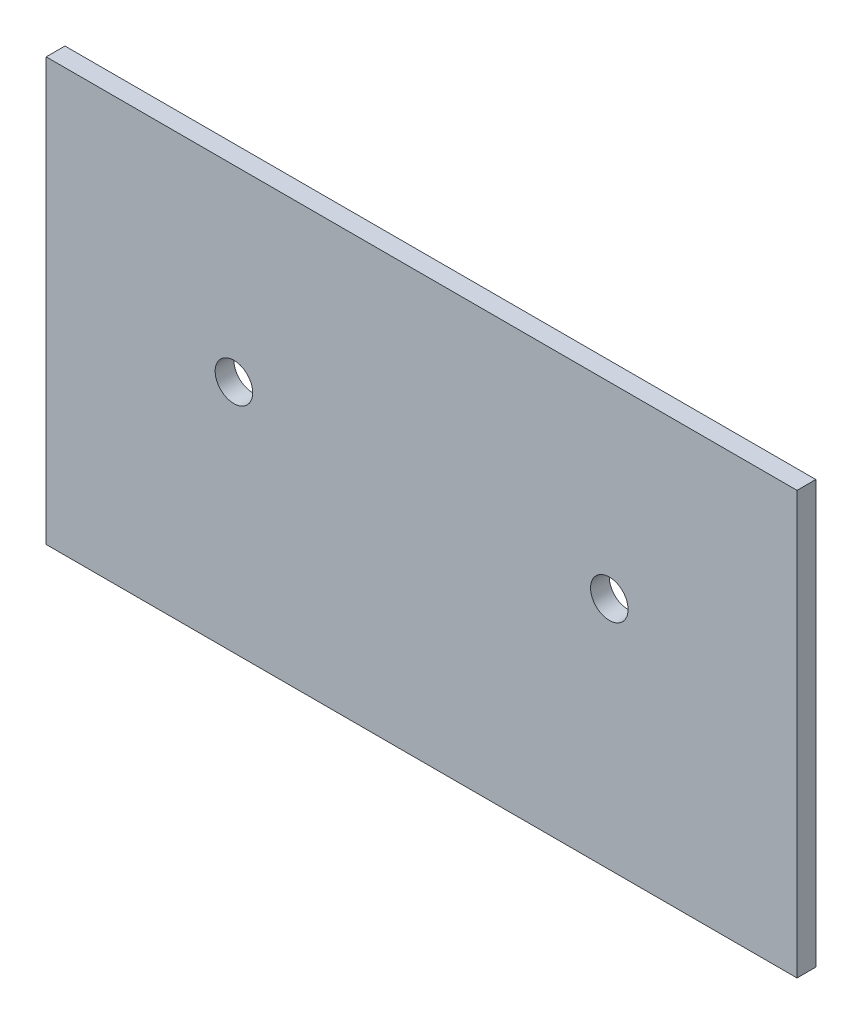
SolidWorks part; units mm, degrees
ref_plane "Front Plane" through (0, 0, 0) normal (0, 0, 1) x (1, 0, 0)
ref_plane "Top Plane" through (0, 0, 0) normal (0, 1, 0) x (1, 0, 0)
ref_plane "Right Plane" through (0, 0, 0) normal (1, 0, 0) x (0, 0, -1)
sketch "Sketch1" plane through (0, 0, 0) normal (0, 0, 1) x (1, 0, 0)
  line L1 (-40, 22.5) -> (40, 22.5)
  line L2 (-40, 22.5) -> (-40, -22.5)
  line L3 (-40, -22.5) -> (40, -22.5)
  line L4 (40, 22.5) -> (40, -22.5)
  line L5 (-40, 22.5) -> (40, -22.5) construction
  line L6 (-40, -22.5) -> (40, 22.5) construction
  point P0 (0, 0)
  dimension "D1" = 45
  dimension "D2" = 80
extrude "Boss-Extrude1" add sketch "Sketch1" along normal blind 2
sketch "Sketch2" plane through (0, 0, 2) normal (0, 0, 1) x (1, 0, 0)
  line L0 (-40, 22.5) -> (-40, -22.5) construction
  line L1 (40, -22.5) -> (40, 22.5) construction
  line L2 (-40, -22.5) -> (40, -22.5) construction
  circle A0 centre (-20, 2.5) radius 2
  circle A1 centre (20, 2.5) radius 2
  dimension "D1" = 4
  dimension "D2" = 4
  dimension "D3" = 20
  dimension "D4" = 20
  dimension "D5" = 25
  dimension "D6" = 25
extrude "Cut-Extrude1" cut sketch "Sketch2" against normal through all
